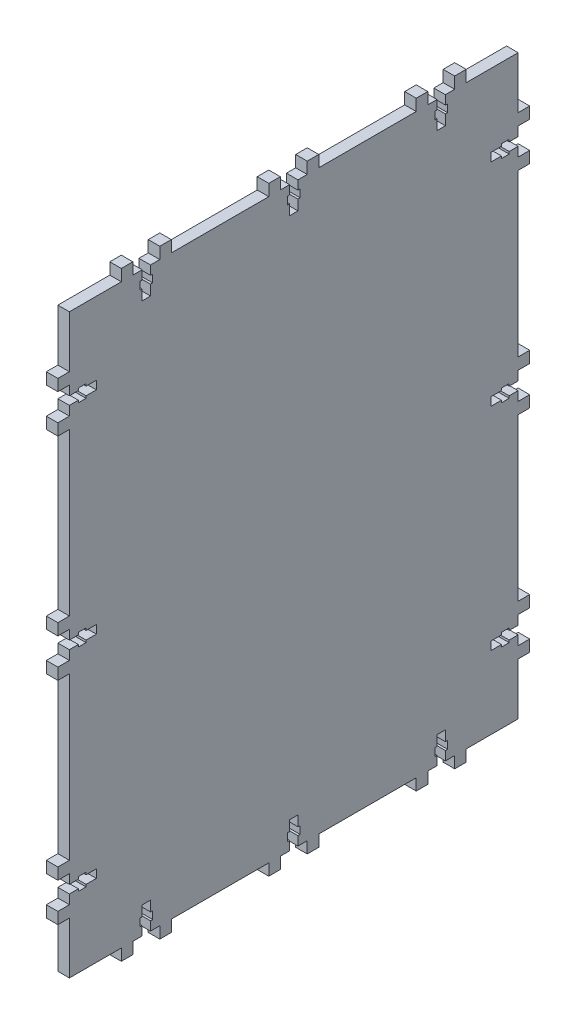
SolidWorks part; units mm, degrees
ref_plane "Front Plane" through (0, 0, 0) normal (0, 0, 1) x (1, 0, 0)
ref_plane "Top Plane" through (0, 0, 0) normal (0, 1, 0) x (1, 0, 0)
ref_plane "Right Plane" through (0, 0, 0) normal (1, 0, 0) x (0, 0, -1)
sketch "Sketch1" plane through (0, 0, 0) normal (1, 0, 0) x (0, 0, -1)
  line L0 (0, 0) -> (0, 185.0898) construction
  line L1 (-175, -225) -> (175, -225)
  line L2 (-175, -225) -> (-175, 225)
  line L3 (-175, 225) -> (175, 225)
  line L4 (175, -225) -> (175, 225)
  line L5 (-175, -225) -> (175, 225) construction
  line L6 (-175, 225) -> (175, -225) construction
  line L7 (0, 0) -> (115.6037, 0) construction
  point P0 (0, 0)
  line B0 (-19.5, -225) -> (-19.5, -234)
  line B1 (-19.5, -234) -> (-10.5, -234)
  line B2 (-10.5, -234) -> (-10.5, -225)
  line B3 (-10.5, -225) -> (-3.25, -225)
  line B4 (-3.25, -225) -> (-3.25, -218)
  line B5 (-3.25, -218) -> (-4.975, -218)
  line B6 (-4.975, -218) -> (-4.975, -212)
  line B7 (-4.975, -212) -> (-3.25, -212)
  line B8 (-3.25, -212) -> (-3.25, -204)
  line B9 (-3.25, -204) -> (3.25, -204)
  line B10 (0, -204) -> (0, -225) construction
  line B11 (3.25, -212) -> (3.25, -204)
  line B12 (4.975, -212) -> (3.25, -212)
  line B13 (4.975, -218) -> (4.975, -212)
  line B14 (3.25, -218) -> (4.975, -218)
  line B15 (3.25, -225) -> (3.25, -218)
  line B16 (10.5, -225) -> (3.25, -225)
  line B17 (10.5, -234) -> (10.5, -225)
  line B18 (19.5, -234) -> (10.5, -234)
  line B19 (19.5, -225) -> (19.5, -234)
  line B20 (175, -19.5) -> (184, -19.5)
  line B21 (184, -19.5) -> (184, -10.5)
  line B22 (184, -10.5) -> (175, -10.5)
  line B23 (175, -10.5) -> (175, -3.25)
  line B24 (175, -3.25) -> (168, -3.25)
  line B25 (168, -3.25) -> (168, -4.975)
  line B26 (168, -4.975) -> (162, -4.975)
  line B27 (162, -4.975) -> (162, -3.25)
  line B28 (162, -3.25) -> (154, -3.25)
  line B29 (154, -3.25) -> (154, 3.25)
  line B30 (154, 0) -> (175, 0) construction
  line B31 (162, 3.25) -> (154, 3.25)
  line B32 (162, 4.975) -> (162, 3.25)
  line B33 (168, 4.975) -> (162, 4.975)
  line B34 (168, 3.25) -> (168, 4.975)
  line B35 (175, 3.25) -> (168, 3.25)
  line B36 (175, 10.5) -> (175, 3.25)
  line B37 (184, 10.5) -> (175, 10.5)
  line B38 (184, 19.5) -> (184, 10.5)
  line B39 (175, 19.5) -> (184, 19.5)
  line B40 (95.5, -225) -> (95.5, -234)
  line B41 (95.5, -234) -> (104.5, -234)
  line B42 (104.5, -234) -> (104.5, -225)
  line B43 (104.5, -225) -> (111.75, -225)
  line B44 (111.75, -225) -> (111.75, -218)
  line B45 (111.75, -218) -> (110.025, -218)
  line B46 (110.025, -218) -> (110.025, -212)
  line B47 (110.025, -212) -> (111.75, -212)
  line B48 (111.75, -212) -> (111.75, -204)
  line B49 (111.75, -204) -> (118.25, -204)
  line B50 (115, -204) -> (115, -225) construction
  line B51 (118.25, -212) -> (118.25, -204)
  line B52 (119.975, -212) -> (118.25, -212)
  line B53 (119.975, -218) -> (119.975, -212)
  line B54 (118.25, -218) -> (119.975, -218)
  line B55 (118.25, -225) -> (118.25, -218)
  line B56 (125.5, -225) -> (118.25, -225)
  line B57 (125.5, -234) -> (125.5, -225)
  line B58 (134.5, -234) -> (125.5, -234)
  line B59 (134.5, -225) -> (134.5, -234)
  line B60 (175, -184.5) -> (184, -184.5)
  line B61 (184, -184.5) -> (184, -175.5)
  line B62 (184, -175.5) -> (175, -175.5)
  line B63 (175, -175.5) -> (175, -168.25)
  line B64 (175, -168.25) -> (168, -168.25)
  line B65 (168, -168.25) -> (168, -169.975)
  line B66 (168, -169.975) -> (162, -169.975)
  line B67 (162, -169.975) -> (162, -168.25)
  line B68 (162, -168.25) -> (154, -168.25)
  line B69 (154, -168.25) -> (154, -161.75)
  line B70 (154, -165) -> (175, -165) construction
  line B71 (162, -161.75) -> (154, -161.75)
  line B72 (162, -160.025) -> (162, -161.75)
  line B73 (168, -160.025) -> (162, -160.025)
  line B74 (168, -161.75) -> (168, -160.025)
  line B75 (175, -161.75) -> (168, -161.75)
  line B76 (175, -154.5) -> (175, -161.75)
  line B77 (184, -154.5) -> (175, -154.5)
  line B78 (184, -145.5) -> (184, -154.5)
  line B79 (175, -145.5) -> (184, -145.5)
  line B80 (-95.5, -225) -> (-95.5, -234)
  line B81 (-95.5, -234) -> (-104.5, -234)
  line B82 (-104.5, -234) -> (-104.5, -225)
  line B83 (-104.5, -225) -> (-111.75, -225)
  line B84 (-111.75, -225) -> (-111.75, -218)
  line B85 (-111.75, -218) -> (-110.025, -218)
  line B86 (-110.025, -218) -> (-110.025, -212)
  line B87 (-110.025, -212) -> (-111.75, -212)
  line B88 (-111.75, -212) -> (-111.75, -204)
  line B89 (-111.75, -204) -> (-118.25, -204)
  line B90 (-115, -204) -> (-115, -225) construction
  line B91 (-118.25, -212) -> (-118.25, -204)
  line B92 (-119.975, -212) -> (-118.25, -212)
  line B93 (-119.975, -218) -> (-119.975, -212)
  line B94 (-118.25, -218) -> (-119.975, -218)
  line B95 (-118.25, -225) -> (-118.25, -218)
  line B96 (-125.5, -225) -> (-118.25, -225)
  line B97 (-125.5, -234) -> (-125.5, -225)
  line B98 (-134.5, -234) -> (-125.5, -234)
  line B99 (-134.5, -225) -> (-134.5, -234)
  line B100 (-175, -184.5) -> (-184, -184.5)
  line B101 (-184, -184.5) -> (-184, -175.5)
  line B102 (-184, -175.5) -> (-175, -175.5)
  line B103 (-175, -175.5) -> (-175, -168.25)
  line B104 (-175, -168.25) -> (-168, -168.25)
  line B105 (-168, -168.25) -> (-168, -169.975)
  line B106 (-168, -169.975) -> (-162, -169.975)
  line B107 (-162, -169.975) -> (-162, -168.25)
  line B108 (-162, -168.25) -> (-154, -168.25)
  line B109 (-154, -168.25) -> (-154, -161.75)
  line B110 (-154, -165) -> (-175, -165) construction
  line B111 (-162, -161.75) -> (-154, -161.75)
  line B112 (-162, -160.025) -> (-162, -161.75)
  line B113 (-168, -160.025) -> (-162, -160.025)
  line B114 (-168, -161.75) -> (-168, -160.025)
  line B115 (-175, -161.75) -> (-168, -161.75)
  line B116 (-175, -154.5) -> (-175, -161.75)
  line B117 (-184, -154.5) -> (-175, -154.5)
  line B118 (-184, -145.5) -> (-184, -154.5)
  line B119 (-175, -145.5) -> (-184, -145.5)
  line B120 (-175, -19.5) -> (-184, -19.5)
  line B121 (-184, -19.5) -> (-184, -10.5)
  line B122 (-184, -10.5) -> (-175, -10.5)
  line B123 (-175, -10.5) -> (-175, -3.25)
  line B124 (-175, -3.25) -> (-168, -3.25)
  line B125 (-168, -3.25) -> (-168, -4.975)
  line B126 (-168, -4.975) -> (-162, -4.975)
  line B127 (-162, -4.975) -> (-162, -3.25)
  line B128 (-162, -3.25) -> (-154, -3.25)
  line B129 (-154, -3.25) -> (-154, 3.25)
  line B130 (-154, 0) -> (-175, 0) construction
  line B131 (-162, 3.25) -> (-154, 3.25)
  line B132 (-162, 4.975) -> (-162, 3.25)
  line B133 (-168, 4.975) -> (-162, 4.975)
  line B134 (-168, 3.25) -> (-168, 4.975)
  line B135 (-175, 3.25) -> (-168, 3.25)
  line B136 (-175, 10.5) -> (-175, 3.25)
  line B137 (-184, 10.5) -> (-175, 10.5)
  line B138 (-184, 19.5) -> (-184, 10.5)
  line B139 (-175, 19.5) -> (-184, 19.5)
  line B140 (-175, 184.5) -> (-184, 184.5)
  line B141 (-184, 184.5) -> (-184, 175.5)
  line B142 (-184, 175.5) -> (-175, 175.5)
  line B143 (-175, 175.5) -> (-175, 168.25)
  line B144 (-175, 168.25) -> (-168, 168.25)
  line B145 (-168, 168.25) -> (-168, 169.975)
  line B146 (-168, 169.975) -> (-162, 169.975)
  line B147 (-162, 169.975) -> (-162, 168.25)
  line B148 (-162, 168.25) -> (-154, 168.25)
  line B149 (-154, 168.25) -> (-154, 161.75)
  line B150 (-154, 165) -> (-175, 165) construction
  line B151 (-162, 161.75) -> (-154, 161.75)
  line B152 (-162, 160.025) -> (-162, 161.75)
  line B153 (-168, 160.025) -> (-162, 160.025)
  line B154 (-168, 161.75) -> (-168, 160.025)
  line B155 (-175, 161.75) -> (-168, 161.75)
  line B156 (-175, 154.5) -> (-175, 161.75)
  line B157 (-184, 154.5) -> (-175, 154.5)
  line B158 (-184, 145.5) -> (-184, 154.5)
  line B159 (-175, 145.5) -> (-184, 145.5)
  line B160 (95.5, 225) -> (95.5, 234)
  line B161 (95.5, 234) -> (104.5, 234)
  line B162 (104.5, 234) -> (104.5, 225)
  line B163 (104.5, 225) -> (111.75, 225)
  line B164 (111.75, 225) -> (111.75, 218)
  line B165 (111.75, 218) -> (110.025, 218)
  line B166 (110.025, 218) -> (110.025, 212)
  line B167 (110.025, 212) -> (111.75, 212)
  line B168 (111.75, 212) -> (111.75, 204)
  line B169 (111.75, 204) -> (118.25, 204)
  line B170 (115, 204) -> (115, 225) construction
  line B171 (118.25, 212) -> (118.25, 204)
  line B172 (119.975, 212) -> (118.25, 212)
  line B173 (119.975, 218) -> (119.975, 212)
  line B174 (118.25, 218) -> (119.975, 218)
  line B175 (118.25, 225) -> (118.25, 218)
  line B176 (125.5, 225) -> (118.25, 225)
  line B177 (125.5, 234) -> (125.5, 225)
  line B178 (134.5, 234) -> (125.5, 234)
  line B179 (134.5, 225) -> (134.5, 234)
  line B180 (-19.5, 225) -> (-19.5, 234)
  line B181 (-19.5, 234) -> (-10.5, 234)
  line B182 (-10.5, 234) -> (-10.5, 225)
  line B183 (-10.5, 225) -> (-3.25, 225)
  line B184 (-3.25, 225) -> (-3.25, 218)
  line B185 (-3.25, 218) -> (-4.975, 218)
  line B186 (-4.975, 218) -> (-4.975, 212)
  line B187 (-4.975, 212) -> (-3.25, 212)
  line B188 (-3.25, 212) -> (-3.25, 204)
  line B189 (-3.25, 204) -> (3.25, 204)
  line B190 (0, 204) -> (0, 225) construction
  line B191 (3.25, 212) -> (3.25, 204)
  line B192 (4.975, 212) -> (3.25, 212)
  line B193 (4.975, 218) -> (4.975, 212)
  line B194 (3.25, 218) -> (4.975, 218)
  line B195 (3.25, 225) -> (3.25, 218)
  line B196 (10.5, 225) -> (3.25, 225)
  line B197 (10.5, 234) -> (10.5, 225)
  line B198 (19.5, 234) -> (10.5, 234)
  line B199 (19.5, 225) -> (19.5, 234)
  line B200 (-95.5, 225) -> (-95.5, 234)
  line B201 (-95.5, 234) -> (-104.5, 234)
  line B202 (-104.5, 234) -> (-104.5, 225)
  line B203 (-104.5, 225) -> (-111.75, 225)
  line B204 (-111.75, 225) -> (-111.75, 218)
  line B205 (-111.75, 218) -> (-110.025, 218)
  line B206 (-110.025, 218) -> (-110.025, 212)
  line B207 (-110.025, 212) -> (-111.75, 212)
  line B208 (-111.75, 212) -> (-111.75, 204)
  line B209 (-111.75, 204) -> (-118.25, 204)
  line B210 (-115, 204) -> (-115, 225) construction
  line B211 (-118.25, 212) -> (-118.25, 204)
  line B212 (-119.975, 212) -> (-118.25, 212)
  line B213 (-119.975, 218) -> (-119.975, 212)
  line B214 (-118.25, 218) -> (-119.975, 218)
  line B215 (-118.25, 225) -> (-118.25, 218)
  line B216 (-125.5, 225) -> (-118.25, 225)
  line B217 (-125.5, 234) -> (-125.5, 225)
  line B218 (-134.5, 234) -> (-125.5, 234)
  line B219 (-134.5, 225) -> (-134.5, 234)
  line B220 (175, 184.5) -> (184, 184.5)
  line B221 (184, 184.5) -> (184, 175.5)
  line B222 (184, 175.5) -> (175, 175.5)
  line B223 (175, 175.5) -> (175, 168.25)
  line B224 (175, 168.25) -> (168, 168.25)
  line B225 (168, 168.25) -> (168, 169.975)
  line B226 (168, 169.975) -> (162, 169.975)
  line B227 (162, 169.975) -> (162, 168.25)
  line B228 (162, 168.25) -> (154, 168.25)
  line B229 (154, 168.25) -> (154, 161.75)
  line B230 (154, 165) -> (175, 165) construction
  line B231 (162, 161.75) -> (154, 161.75)
  line B232 (162, 160.025) -> (162, 161.75)
  line B233 (168, 160.025) -> (162, 160.025)
  line B234 (168, 161.75) -> (168, 160.025)
  line B235 (175, 161.75) -> (168, 161.75)
  line B236 (175, 154.5) -> (175, 161.75)
  line B237 (184, 154.5) -> (175, 154.5)
  line B238 (184, 145.5) -> (184, 154.5)
  line B239 (175, 145.5) -> (184, 145.5)
  dimension "D1" = 450
  dimension "D2" = 350
  dimension "D3" = 60
  dimension "D4" = 60
sketch_block_instance "Plot_9mm_M6_bois-1"
sketch_block "Plot_9mm_M6_bois" parameters "D1"=9, "D2"=9, "D3"=16, "D4"=30, "D5"=9.95, "D6"=6.5, "D7"=6, "D8"=8
sketch_block_instance "Plot_9mm_M6_bois-2"
sketch_block_instance "Plot_9mm_M6_bois-4"
sketch_block_instance "Plot_9mm_M6_bois-5"
sketch_block_instance "Plot_9mm_M6_bois-6"
sketch_block_instance "Plot_9mm_M6_bois-7"
sketch_block_instance "Plot_9mm_M6_bois-8"
sketch_block_instance "Plot_9mm_M6_bois-9"
sketch_block_instance "Plot_9mm_M6_bois-10"
sketch_block_instance "Plot_9mm_M6_bois-11"
sketch_block_instance "Plot_9mm_M6_bois-12"
sketch_block_instance "Plot_9mm_M6_bois-13"
extrude "Boss-Extrude1" add sketch "Sketch1" along normal blind 9 contours L4 B235 B234 B233 B232 B231 B229 B228 B227 B226 B225 B224 L3 B175 B174 B173 B172 B171 B169 B168 B167 B166 B165 B164 B195 B194 B193 B192 B191 B189 B188 B187 B186 B185 B184 | B162 B161 B160 L3 | L3 B179 B178 B177 | B222 B221 B220 L4 | L4 B239 B238 B237 | L3 B199 B198 B197 | B182 B181 B180 L3 | B219 L3 B217 B218 | B201 B202 L3 B200 | B141 B142 L2 B140 | B159 L2 B157 B158 | B122 B121 B120 L2 | L2 B139 B138 B137 | L2 B119 B118 B117 | B102 B101 B100 L2 | L1 B99 B98 B97 | B82 B81 B80 L1 | B1 B2 L1 B0 | B19 L1 B17 B18 | B41 B42 L1 B40 | B59 L1 B57 B58 | B61 B62 L4 B60 | B79 L4 B77 B78 | B39 L4 B37 B38 | B21 B22 L4 B20
